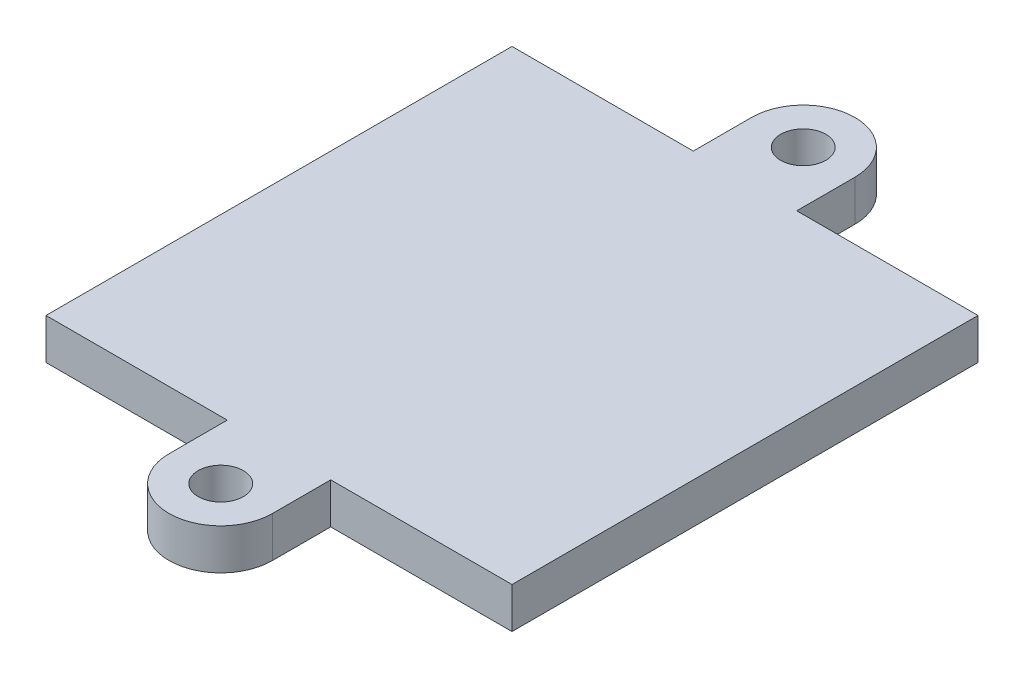
SolidWorks part; units mm, degrees
ref_plane "Front Plane" through (0, 0, 0) normal (0, 0, 1) x (1, 0, 0)
ref_plane "Top Plane" through (0, 0, 0) normal (0, 1, 0) x (1, 0, 0)
ref_plane "Right Plane" through (0, 0, 0) normal (1, 0, 0) x (0, 0, -1)
sketch "Sketch1" plane through (0, 0, 0) normal (0, 1, 0) x (1, 0, 0)
  line L0 (-25.4, 25.4) -> (-5.6388, 25.4)
  line L1 (-19.05, 19.05) -> (19.05, 19.05) construction
  line L2 (-19.05, 19.05) -> (-19.05, -19.05) construction
  line L3 (-19.05, -19.05) -> (19.05, -19.05) construction
  line L4 (19.05, 19.05) -> (19.05, -19.05) construction
  line L5 (-19.05, 19.05) -> (19.05, -19.05) construction
  line L6 (-19.05, -19.05) -> (19.05, 19.05) construction
  line L7 (25.4, 25.4) -> (25.4, -25.4)
  line L8 (-25.4, -25.4) -> (-5.6388, -25.4)
  line L9 (-25.4, 25.4) -> (-25.4, -25.4)
  line L10 (-5.6388, 31.75) -> (-5.6388, 25.4)
  line L11 (5.6388, 31.75) -> (5.6388, 25.4)
  line L12 (-51.0559, 0) -> (61.0714, 0) construction
  line L13 (-5.6388, -31.75) -> (-5.6388, -25.4)
  line L14 (5.6388, -31.75) -> (5.6388, -25.4)
  line L15 (5.6388, 25.4) -> (25.4, 25.4)
  line L16 (-25.4, 25.4) -> (25.4, 25.4) construction
  line L17 (5.6388, -25.4) -> (25.4, -25.4)
  line L18 (-25.4, -25.4) -> (25.4, -25.4) construction
  circle A0 centre (0, 31.75) radius 2.4638
  arc A1 (5.6388, 31.75) -> (-5.6388, 31.75) centre (0, 31.75) ccw
  circle A2 centre (0, -31.75) radius 2.4638
  arc A3 (5.6388, -31.75) -> (-5.6388, -31.75) centre (0, -31.75) cw
  circle A4 centre (0, 31.75) radius 5.6388 construction
  point P0 (0, 0)
  dimension "D4" = 4.9276
  dimension "D1" = 38.1
  dimension "D2" = 38.1
  dimension "D6" = 31.75
  dimension "D3" = 6.35
  dimension "D5" = 3.175
extrude "Boss-Extrude1" add sketch "Sketch1" along normal blind 4.445 contours A3 L14 L17 L7 L15 L11 A1 L10 L0 L9 L8 L13 A0 A2
